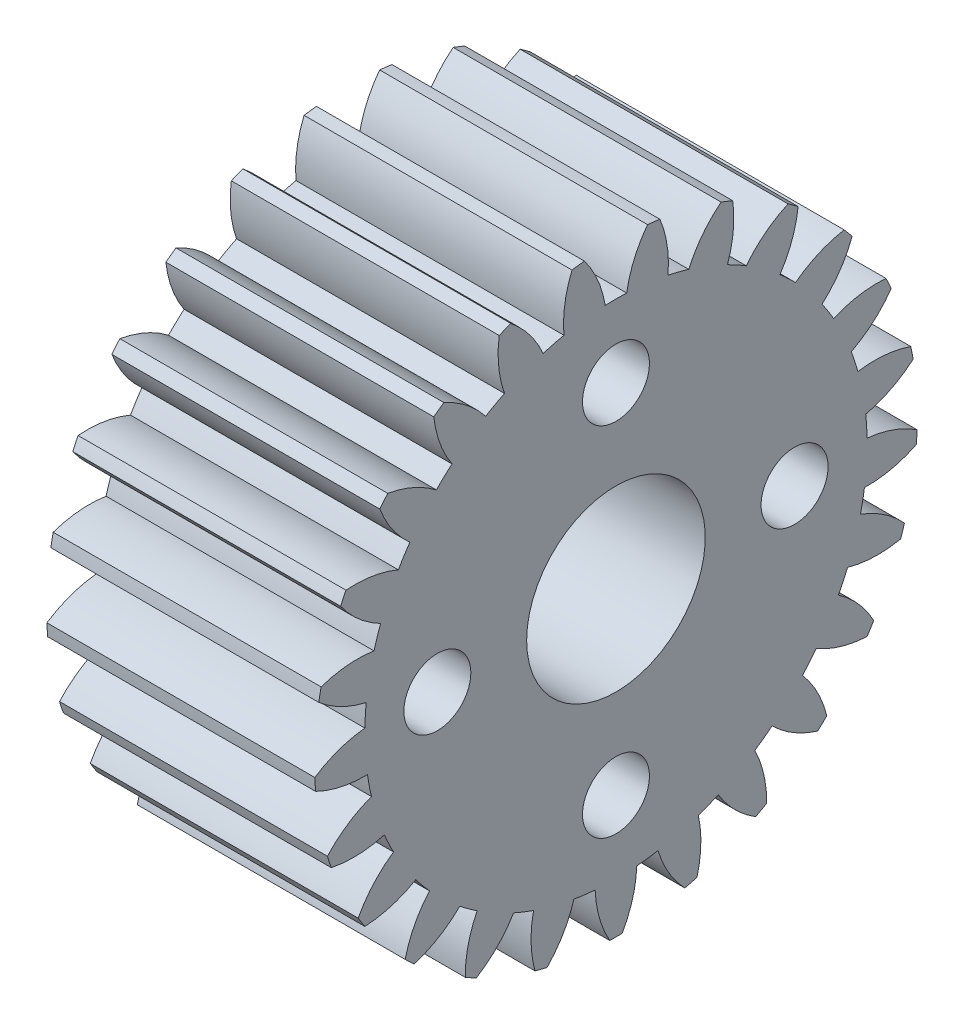
SolidWorks part; units mm, degrees
ref_plane "Plane1" through (0, 0, 0) normal (0, 0, 1) x (1, 0, 0)
ref_plane "Plane2" through (0, 0, 0) normal (0, 1, 0) x (1, 0, 0)
ref_plane "Plane3" through (0, 0, 0) normal (1, 0, 0) x (0, 0, -1)
sketch "HoldingSke" plane through (0, 0, 0) normal (0, 1, 0) x (1, 0, 0)
  line L0 (0, 0) -> (0.9063, -0.4226)
  line L1 (-15, 0) -> (100, 0) construction
  line L2 (0, 0) -> (-2.1039, 2.3779)
  line L3 (0, 0) -> (-11.863, 4.5341)
  line L4 (0, 0) -> (7.8269, 3.6497)
  line L5 (0, 0) -> (-46.8476, -17.4728)
  line L6 (0, 0) -> (-9.9476, -6.7116)
  line L7 (-2.1039, 2.3779) -> (8.6586, 51.2059)
  line L8 (-76.2, 54.61) -> (-74.8, 54.61)
  line L9 (-71.009, 38.7566) -> (-53.1078, 45.2721)
  line L10 (-76.2, 71.12) -> (104.1128, 71.12)
  line L11 (0, 0) -> (-12, 0)
  line L12 (-76.2, 101.6) -> (-76.162, 101.6)
  line L13 (24.9733, 27.94) -> (52.9518, 28.4284)
  line L14 (24.9733, 27.94) -> (24.9743, 27.94)
  line L15 (24.9733, 27.94) -> (100.4006, 29.5858)
  line L16 (-63.627, -1) -> (-12.827, -1)
  circle A0 centre (0, 0) radius 4
  circle A1 centre (0, 0) radius 11.249
  circle A2 centre (0, 0) radius 37.5
  circle A3 centre (0, 0) radius 4
  dimension "MHD" = 22.498
  dimension "Hub_dia" = 75
  dimension "Bore" = 8
  dimension "MBD" = 8
  dimension "Num_teeth" = 25
  dimension "Pitch" = 1
  dimension "Overall_len" = 50
  dimension "Show_teeth" = 25
  dimension "Thickness" = 12
  dimension "OAL" = 50.0001
  dimension "T_dim" = 1.4
  dimension "Ap" = 20
  dimension "H" = 19.05
  dimension "Pitch_radius" = 180.3128
  dimension "Width" = 12
  dimension "Backlash" = 0.038
  dimension "Addendum_fac" = 1
  dimension "Dedendum_fac" = 1.25
  dimension "Clearance_fac" = 0.25
  dimension "Dedendum_add" = 0.001
  dimension "Module" = 1
sketch "BasProSke" plane through (0, 0, 0) normal (0, 1, 0) x (1, 0, 0)
  line L0 (-10, 0) -> (60, 0) construction
  line L1 (0, 0) -> (0, 13.5)
  line L2 (0, 0) -> (12, 0)
  line L3 (12, 0) -> (12, 13.5)
  line L4 (12, 13.5) -> (0, 13.5)
  dimension "Thickness" = 12
  dimension "Diameter" = 27
revolve "Base-Revolve" add sketch "BasProSke" angle 360 about L0
sketch "TooCutSke" plane through (0, 0, 0) normal (1, 0, 0) x (0, 0, -1)
  line L1 (0, 0) -> (0, 107) construction
  line L2 (0, 0) -> (-0.8514, 12.471) construction
  line L3 (0, 0) -> (-3.1282, 24.7619) construction
  line L4 (-0.8514, 12.471) -> (-1.5641, 12.3809) construction
  arc A0 (0.4801, 11.2388) -> (-0.4801, 11.2388) centre (0, 0) ccw
  arc A1 (1.4322, 13.4494) -> (-1.4322, 13.4494) centre (0, 0) ccw
  circle A2 centre (0, 0) radius 12.5 construction
  circle A3 centre (0, 0) radius 11.7462 construction
  arc A4 (-0.4801, 11.2388) -> (-1.4322, 13.4494) centre (-5.4133, 10.4244) ccw
  arc A5 (1.4322, 13.4494) -> (0.4801, 11.2388) centre (5.4133, 10.4244) ccw
  dimension "Root_dia" = 22.498
  dimension "Overcut_dia" = 27.0508
  dimension "Pitch_dia" = 25
  dimension "Base_dia" = 23.4923
  dimension "Flank_rad" = 5
  dimension "Half_ang" = 7.2
  dimension "Half_CT" = 0.7184
extrude "ToothCut" cut sketch "TooCutSke" along normal through all
fillet "Breaks" [suppressed] radius 0.02
fillet "RootFillets" [suppressed] radius 0.251
pattern_circular "TeethCuts" count 25 every 14.4 about axis through (-10, 0, 0) along (1, 0, 0) of "ToothCut", "RootFillets", "Breaks"
sketch "HubNeaOneSke" plane through (0, 0, 0) normal (-1, 0, 0) x (0, 0, 1)
  circle A0 centre (0, 0) radius 11.249
  dimension "Diameter" = 22.498
extrude "HubNearOne" [suppressed] add sketch "HubNeaOneSke" along normal blind 38.0001
sketch "HubNeaBotSke" plane through (0, 0, 0) normal (-1, 0, 0) x (0, 0, 1)
  circle A0 centre (0, 0) radius 11.249
  dimension "Diameter" = 22.498
extrude "HubNearBoth" [suppressed] add sketch "HubNeaBotSke" along normal blind 19
ref_plane "FarPln" through (12, 0, 0) normal (1, 0, 0) x (0, 0, -1)
sketch "HubFarSke" plane through (12, 0, 0) normal (1, 0, 0) x (0, 0, -1)
  circle A0 centre (0, 0) radius 11.249
  dimension "Diameter" = 22.498
extrude "HubFar" [suppressed] add sketch "HubFarSke" along normal blind 19
sketch "BorSke" plane through (0, 0, 0) normal (1, 0, 0) x (0, 0, -1)
  circle A0 centre (0, 0) radius 4
  point P4 (0, 8)
  dimension "Diameter" = 8
extrude "Bore" cut sketch "BorSke" along normal mid plane 100.0001
sketch "KeySke" plane through (0, 0, 0) normal (1, 0, 0) x (0, 0, -1)
  line L0 (-1, 0) -> (-1, 5.4)
  line L1 (-1, 5.4) -> (1, 5.4)
  line L2 (1, 5.4) -> (1, 0)
  line L3 (0, 0) -> (0, 34) construction
  line L4 (-1, 0) -> (1, 0)
  dimension "Offset" = 5.4
  dimension "Width" = 2
extrude "Keyway" [suppressed] cut sketch "KeySke" along normal mid plane 100.0001
pattern_circular "Keyway2" [suppressed] count 2 every 90 about axis through (-10, 0, 0) along (1, 0, 0)
sketch "Sketch1" plane through (12, 0, 0) normal (1, 0, 0) x (0, 0, -1)
  circle A0 centre (0, 8) radius 1.5
  circle A1 centre (8, 0) radius 1.5
  circle A2 centre (0, -8) radius 1.5
  circle A3 centre (-8, 0) radius 1.5
  point P2 (-8.7464, -0.7324)
  point P3 (0, 0)
  point P12 (0, 0)
  dimension "D1" = 3
  dimension "D2" = 8
extrude "Cut-Extrude1" cut sketch "Sketch1" against normal through all
equation "' \"Module@HoldingSke\" = 6.35"
equation "' \"Num_teeth@HoldingSke\" = 12"
equation "' \"Ap@HoldingSke\" =  20"
equation "' \"Ap@HoldingSke\" = 20"
equation "' \"Width@HoldingSke\" = 0.5 * 25.4"
equation "' \"Hub_dia@HoldingSke\"= 1 * 25.4"
equation "' \"Hub_dia@HoldingSke\" = 1 * 25.4"
equation "' \"Overall_len@HoldingSke\" = 1.0 * 25.4"
equation "' \"Bore@HoldingSke\" = 0.75 * 25.4"
equation "' \"T_dim@HoldingSke\" = 0.1 * 25.4"
equation "' \"Width@KeySke\" = 0.25 * 25.4"
equation "' \"Show_teeth@HoldingSke\" = 13"
equation "' \"Backlash@HoldingSke\" = 0.009 * 25.4"
equation "' \"Addendum_fac@HoldingSke\" = 1.0"
equation "' \"Dedendum_fac@HoldingSke\" = 1.25"
equation "' \"Dedendum_add@HoldingSke\" = 0.00005 * 25.4"
equation "' \"Clearance_fac@HoldingSke\" = 0.25"
equation "\"Pitch@HoldingSke\" = 1 / \"Module@HoldingSke\""
equation "\"Overcut_dia@TooCutSke\" = (\"Num_teeth@HoldingSke\" + 2 * \"Addendum_fac@HoldingSke\") / \"Pitch@HoldingSke\" + 0.002 * 25.4"
equation "\"Pitch_dia@TooCutSke\" = \"Num_teeth@HoldingSke\" / \"Pitch@HoldingSke\""
equation "\"Base_dia@TooCutSke\" = \"Num_teeth@HoldingSke\" / \"Pitch@HoldingSke\" * cos((\"Ap@HoldingSke\"  * 3.14159265 / 180))"
equation "\"Root_dia@TooCutSke\" = (\"Num_teeth@HoldingSke\" + 2) / \"Pitch@HoldingSke\" - 2 * (\"Addendum_fac@HoldingSke\" + \"Dedendum_fac@HoldingSke\") / \"Pitch@HoldingSke\" - \"Dedendum_add@HoldingSke\" * 2"
equation "\"Half_ang@TooCutSke\" = 180 / \"Num_teeth@HoldingSke\""
equation "\"Half_CT@TooCutSke\" = \"Num_teeth@HoldingSke\" / \"Pitch@HoldingSke\" * sin((3.14159265 / 2 / \"Num_teeth@HoldingSke\")) / 2 - 7 * \"Backlash@HoldingSke\" / 4"
equation "\"Flank_rad@TooCutSke\" = \"Num_teeth@HoldingSke\" / \"Pitch@HoldingSke\" / 5"
equation "\"Radius@RootFillets\" = \"Clearance_fac@HoldingSke\" / \"Pitch@HoldingSke\" + \"Dedendum_add@HoldingSke\""
equation "\"Break_rad@Breaks\" = 0.02 / \"Pitch@HoldingSke\""
equation "\"Thickness@HoldingSke\" = \"Width@HoldingSke\""
equation "\"OAL@HoldingSke\" = \"Thickness@HoldingSke\""
equation "\"MHD@HoldingSke\" = (\"Num_teeth@HoldingSke\" + 2) / \"Pitch@HoldingSke\" - 2 * (\"Addendum_fac@HoldingSke\" + \"Dedendum_fac@HoldingSke\")  / \"Pitch@HoldingSke\" - \"Dedendum_add@HoldingSke\" * 2"
equation "\"MBD@HoldingSke\" = (\"Num_teeth@HoldingSke\" + 2) / \"Pitch@HoldingSke\" - 2 * (\"Addendum_fac@HoldingSke\" + \"Dedendum_fac@HoldingSke\")  / \"Pitch@HoldingSke\" - \"Dedendum_add@HoldingSke\" * 2 - 0.002 * 25.4"
equation "\"MHD@HoldingSke\" = ((sgn( \"MHD@HoldingSke\" - \"Hub_dia@HoldingSke\" )-1)*( \"MHD@HoldingSke\" - \"Hub_dia@HoldingSke\" ))/-2+ \"Hub_dia@HoldingSke\""
equation "\"MBD@HoldingSke\" = ((sgn( \"MBD@HoldingSke\" - \"Bore@HoldingSke\" )-1)*( \"MBD@HoldingSke\" - \"Bore@HoldingSke\" ))/-2+ \"Bore@HoldingSke\""
equation "\"OAL@HoldingSke\" = ((sgn( \"OAL@HoldingSke\" - \"Overall_len@HoldingSke\" )+1)*( \"OAL@HoldingSke\" - \"Overall_len@HoldingSke\" ))/2 + \"Overall_len@HoldingSke\" + 0.000002 * 25.4"
equation "\"Num_teeth@TeethCuts\" = int( \"Show_teeth@HoldingSke\" ) + 1"
equation "\"Num_teeth@TeethCuts\" = ((sgn( \"Num_teeth@TeethCuts\" - \"Num_teeth@HoldingSke\" )-1)*( \"Num_teeth@TeethCuts\" - \"Num_teeth@HoldingSke\" ))/-2+ \"Num_teeth@HoldingSke\""
equation "\"Num_teeth@TeethCuts\" = ((sgn( \"Num_teeth@TeethCuts\" - 2.0)+1)*( \"Num_teeth@TeethCuts\" - 2.0))/2 +2.0"
equation "\"Angle@TeethCuts\" = 360.0 / \"Num_teeth@HoldingSke\""
equation "\"Diameter@BasProSke\" = (\"Num_teeth@HoldingSke\" + 2 * \"Addendum_fac@HoldingSke\") / \"Pitch@HoldingSke\""
equation "\"Thickness@BasProSke\"  = \"Thickness@HoldingSke\""
equation "' \"Fillet_rad@BasProSke\" =  \"Thickness@HoldingSke\" * 0.05"
equation "' \"Fillet_rad@BasProSke\" = \"Thickness@HoldingSke\" * 0.05"
equation "\"MHD@HoldingSke\" = ((sgn( \"MHD@HoldingSke\" - \"Root_dia@TooCutSke\" )-1)*( \"MHD@HoldingSke\" - \"Root_dia@TooCutSke\" ))/-2+ \"Root_dia@TooCutSke\""
equation "\"Diameter@HubNeaOneSke\" = \"MHD@HoldingSke\""
equation "\"Length@HubNearOne\" = \"OAL@HoldingSke\" - \"Thickness@BasProSke\""
equation "\"Diameter@HubNeaBotSke\" = \"MHD@HoldingSke\""
equation "\"Length@HubNearBoth\" = ( \"OAL@HoldingSke\" - \"Thickness@BasProSke\" ) / 2.0"
equation "\"Thickness@FarPln\" = \"Thickness@BasProSke\""
equation "\"Diameter@HubFarSke\" = \"MHD@HoldingSke\""
equation "\"Length@HubFar\" = ( \"OAL@HoldingSke\" - \"Thickness@BasProSke\" ) / 2.0"
equation "\"Diameter@BorSke\" = \"MBD@HoldingSke\""
equation "\"D1@Bore\" = \"OAL@HoldingSke\" * 2.0"
equation "\"D1@Keyway\" = \"OAL@HoldingSke\" * 2.0"
equation "\"Offset@KeySke\" = \"T_dim@HoldingSke\" + \"MBD@HoldingSke\" / 2.0"
